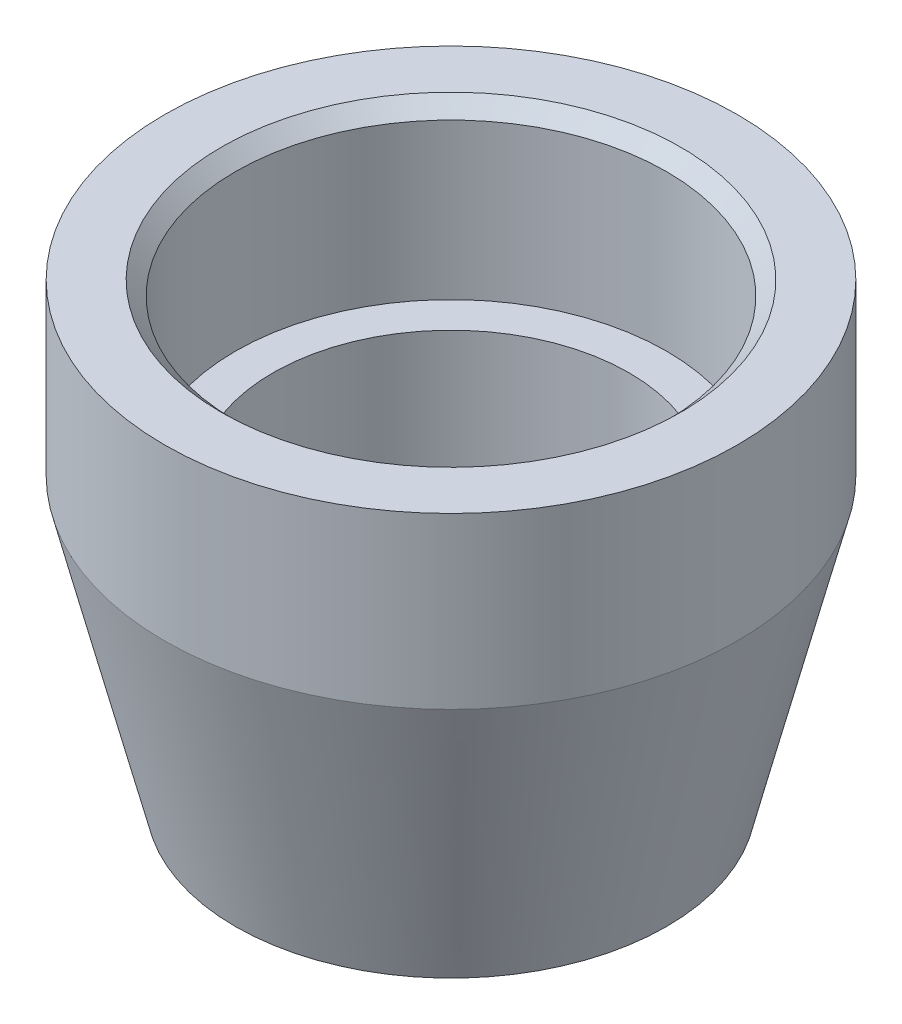
SolidWorks part; units mm, degrees
ref_plane "Front Plane" through (0, 0, 0) normal (0, 0, 1) x (1, 0, 0)
ref_plane "Top Plane" through (0, 0, 0) normal (0, 1, 0) x (1, 0, 0)
ref_plane "Right Plane" through (0, 0, 0) normal (1, 0, 0) x (0, 0, -1)
sketch "Sketch1" plane through (0, 0, 0) normal (0, 0, 1) x (1, 0, 0)
  line L0 (0, 0) -> (0, 15699.7463) construction
  line L1 (2.52, 0) -> (2.52, 4)
  line L2 (2.52, 4) -> (3.05, 4)
  line L3 (3.05, 4) -> (3.05, 6.4)
  line L4 (3.05, 6.4) -> (4.05, 6.4)
  line L5 (4.05, 6.4) -> (4.05, 4)
  line L6 (4.05, 4) -> (3.05, 0)
  line L7 (3.05, 0) -> (2.52, 0)
  point P9 (2.52, 2)
  point P11 (8, 4)
  point P12 (8, 4)
  point P13 (6, 0)
  dimension "D1" = 2.52
  dimension "D2" = 3.05
  dimension "D3" = 1
  dimension "D4" = 2.4
  dimension "D5" = 4
revolve "Revolve1" add sketch "Sketch1" angle 360 about L0
chamfer "Chamfer1" distance 0.2 angle 45 1 edges at (0, 6.4, -3.05)
